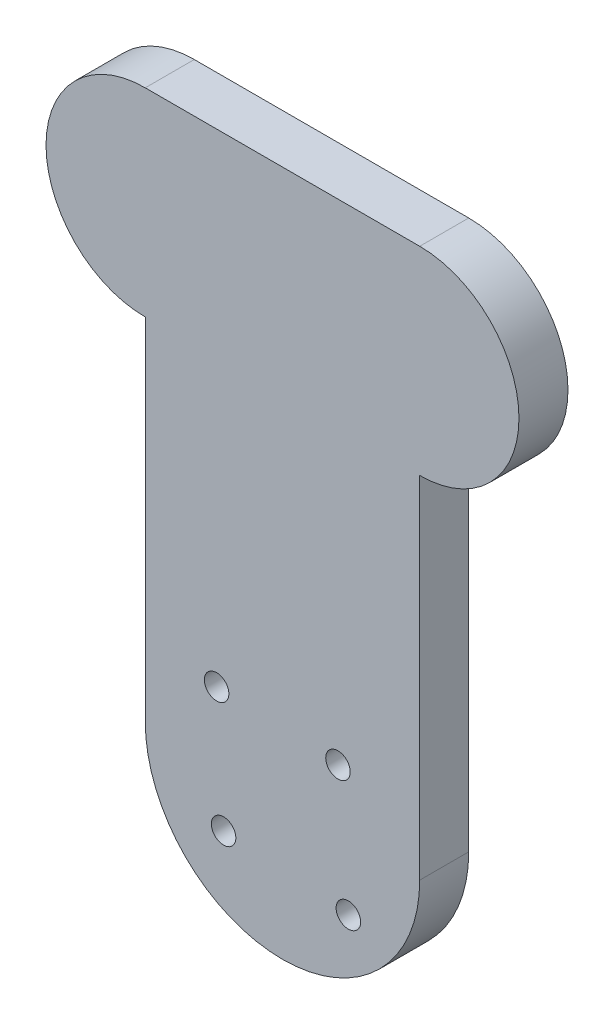
SolidWorks part; units mm, degrees
ref_plane "Front Plane" through (0, 0, 0) normal (0, 0, 1) x (1, 0, 0)
ref_plane "Top Plane" through (0, 0, 0) normal (0, 1, 0) x (1, 0, 0)
ref_plane "Right Plane" through (0, 0, 0) normal (1, 0, 0) x (0, 0, -1)
sketch "Sketch1" plane through (0, 0, 0) normal (0, 0, 1) x (1, 0, 0)
  line L0 (-14, 0) -> (-14, 35.7522)
  line L1 (0, 0) -> (0, 44.3811) construction
  line L2 (14, 0) -> (14, 35.7522)
  line L3 (-14, 56.0011) -> (14, 56.0011)
  arc A0 (-14, 0) -> (14, 0) centre (0, 0) ccw
  arc A1 (-14, 35.7522) -> (-14, 56.0011) centre (-14, 45.8766) cw
  arc A2 (14, 35.7522) -> (14, 56.0011) centre (14, 45.8766) ccw
  circle A3 centre (6.72, -6.72) radius 1.25
  circle A4 centre (-6.01, -5.66) radius 1.25
  circle A5 centre (5.66, 6.01) radius 1.25
  circle A6 centre (-6.72, 6.72) radius 1.25
  dimension "D1" = 2.5
  dimension "D3" = 14
extrude "Boss-Extrude1" add sketch "Sketch1" along normal blind 5
